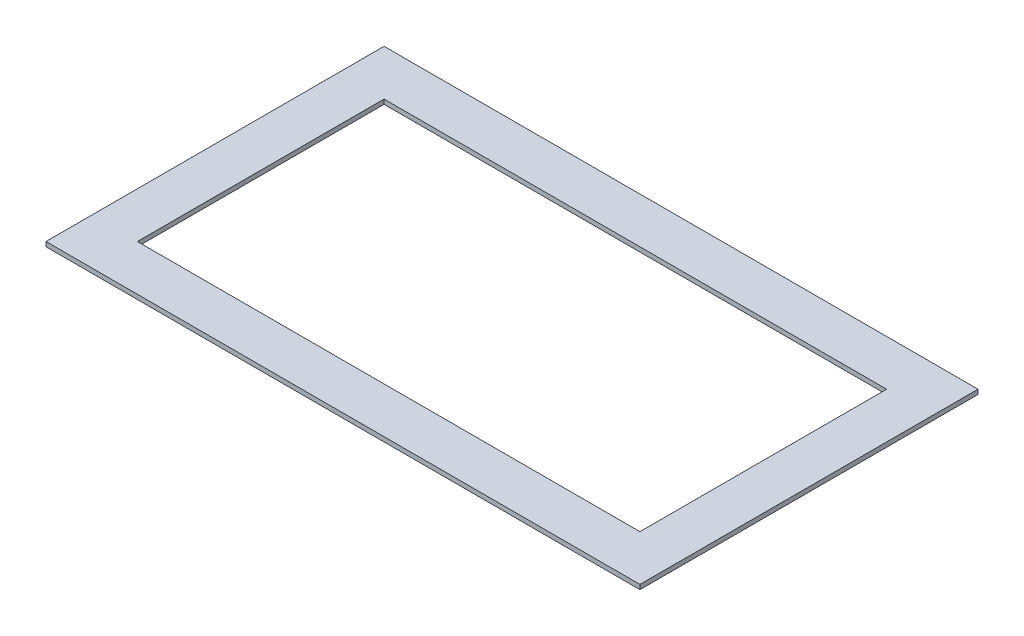
SolidWorks part; units mm, degrees
ref_plane "前视基准面" through (0, 0, 0) normal (0, 0, 1) x (1, 0, 0)
ref_plane "上视基准面" through (0, 0, 0) normal (0, 1, 0) x (1, 0, 0)
ref_plane "右视基准面" through (0, 0, 0) normal (1, 0, 0) x (0, 0, -1)
sketch "草图1" plane through (0, 0, 0) normal (0, 1, 0) x (1, 0, 0)
  line L0 (-27.5, 13.5) -> (27.5, 13.5)
  line L1 (-32.5, 18.5) -> (32.5, 18.5)
  line L2 (-32.5, 18.5) -> (-32.5, -18.5)
  line L3 (-32.5, -18.5) -> (32.5, -18.5)
  line L4 (32.5, 18.5) -> (32.5, -18.5)
  line L5 (-32.5, 18.5) -> (32.5, -18.5) construction
  line L6 (-32.5, -18.5) -> (32.5, 18.5) construction
  line L7 (27.5, 13.5) -> (27.5, -13.5)
  line L8 (-27.5, -13.5) -> (27.5, -13.5)
  line L9 (-27.5, 13.5) -> (-27.5, -13.5)
  point P0 (0, 0)
  dimension "D1" = 65
  dimension "D2" = 37
  dimension "D3" = 5
extrude "凸台-拉伸1" add sketch "草图1" along normal blind 0.5
